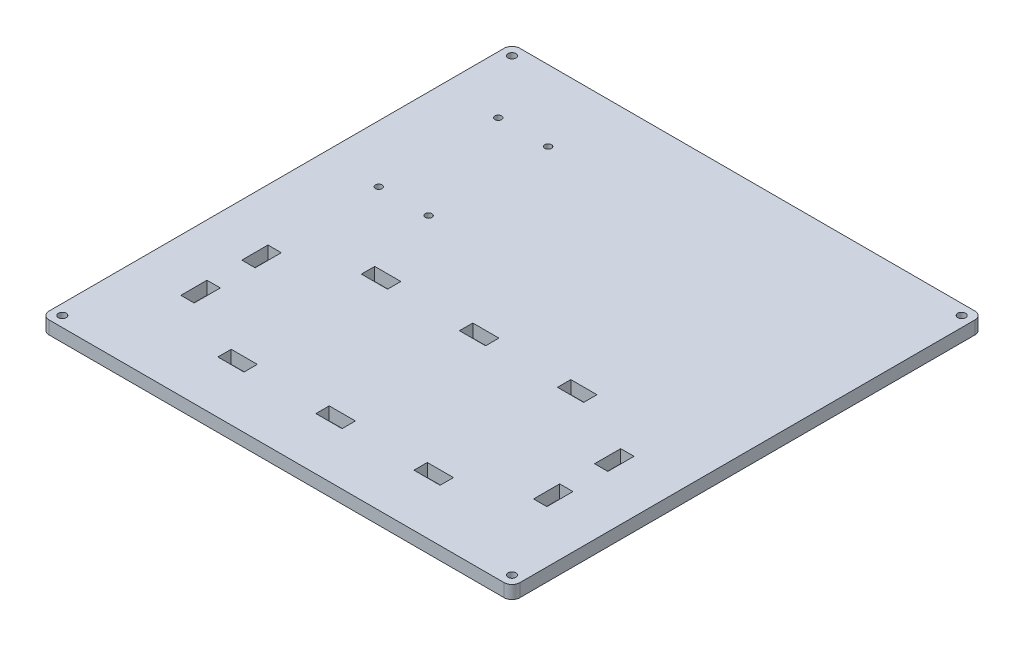
SolidWorks part; units mm, degrees
ref_plane "Front Plane" through (0, 0, 0) normal (0, 0, 1) x (1, 0, 0)
ref_plane "Top Plane" through (0, 0, 0) normal (0, 1, 0) x (1, 0, 0)
ref_plane "Right Plane" through (0, 0, 0) normal (1, 0, 0) x (0, 0, -1)
sketch "Sketch1" plane through (0, 0, 0) normal (0, 1, 0) x (1, 0, 0)
  line L1 (-90, -90) -> (90, -90)
  line L2 (-90, -90) -> (-90, 90)
  line L3 (-90, 90) -> (90, 90)
  line L4 (90, -90) -> (90, 90)
  line L5 (-90, -90) -> (90, 90) construction
  line L6 (-90, 90) -> (90, -90) construction
  line L7 (-70, 65.4) -> (-47.3, 65.4)
  line L8 (-70, 65.4) -> (-70, 14.6)
  line L9 (-70, 14.6) -> (-47.3, 14.6)
  line L10 (-47.3, 65.4) -> (-47.3, 14.6)
  line L11 (-70, 65.4) -> (-47.3, 14.6) construction
  line L12 (-70, 14.6) -> (-47.3, 65.4) construction
  circle A0 centre (-86, 86) radius 1.5
  circle A1 centre (86, 86) radius 1.5
  circle A2 centre (86, -86) radius 1.5
  circle A3 centre (-86, -86) radius 1.5
  circle A4 centre (-68.095, 62.86) radius 1.27
  circle A5 centre (-49.045, 62.86) radius 1.27
  circle A6 centre (-49.045, 17.14) radius 1.27
  circle A7 centre (-68.095, 17.14) radius 1.27
  point P0 (0, 0)
  point P6 (-58.65, 40)
  dimension "D7" = 3
  dimension "D8" = 4
  dimension "D11" = 2.54
  dimension "D13" = 2.54
  dimension "D17" = 2.54
  dimension "D20" = 4
  dimension "D1" = 180
  dimension "D2" = 180
  dimension "D3" = 22.7
  dimension "D4" = 50.8
  dimension "D5" = 24.6
  dimension "D6" = 20
  dimension "D9" = 2
  dimension "D12" = 1.905
  dimension "D16" = 4
  dimension "D18" = 4
  dimension "D19" = 4
  dimension "D10" = 2
  dimension "D14" = 2
  dimension "D15" = 2
extrude "Boss-Extrude1" add sketch "Sketch1" along normal blind 5 contours L1 L4 L3 L2 A3 A2 A1 A0 L7 L10 L9 L8 | L10 L7 L8 L9 A7 A6 A5 A4
sketch "Sketch3" plane through (0, 5, 0) normal (0, 1, 0) x (1, 0, 0)
  line L0 (90, -90) -> (90, 90) construction
  line L1 (20, 85) -> (80, 85)
  line L2 (20, 85) -> (20, 5)
  line L3 (20, 5) -> (80, 5)
  line L4 (80, 85) -> (80, 5)
  line L5 (-90, 90) -> (90, 90) construction
  dimension "D1" = 80
  dimension "D2" = 60
  dimension "D3" = 10
  dimension "D4" = 5
extrude "Boss-Extrude2" [suppressed] add sketch "Sketch3" along normal blind 5
sketch "Sketch4" plane through (0, 5, 0) normal (0, 1, 0) x (1, 0, 0)
  line L0 (-90, -90) -> (90, -90) construction
  line L5 (70, -60) -> (90, -60) construction
  line L6 (90, -90) -> (90, 90) construction
  line L7 (-32.5, -10) -> (-5, -10)
  line L8 (-70, -60) -> (-90, -60) construction
  line L9 (-42.5, -10) -> (-32.5, -10)
  line L10 (-42.5, -10) -> (-42.5, -15.1)
  line L11 (-42.5, -15.1) -> (-32.5, -15.1)
  line L12 (-32.5, -10) -> (-32.5, -15.1)
  line L13 (-5, -10) -> (5, -10)
  line L14 (-5, -10) -> (-5, -15.1)
  line L15 (-5, -15.1) -> (5, -15.1)
  line L16 (5, -10) -> (5, -15.1)
  line L17 (32.5, -10) -> (42.5, -10)
  line L18 (32.5, -10) -> (32.5, -15.1)
  line L19 (32.5, -15.1) -> (42.5, -15.1)
  line L20 (42.5, -10) -> (42.5, -15.1)
  line L21 (-90, -90) -> (-90, 90) construction
  line L22 (-42.5, -64.9) -> (-42.5, -70)
  line L23 (-70, -23.3333) -> (-64.9, -23.3333)
  line L24 (-70, -23.3333) -> (-70, -33.3333)
  line L25 (-70, -33.3333) -> (-64.9, -33.3333)
  line L26 (-64.9, -23.3333) -> (-64.9, -33.3333)
  line L31 (-70, -46.6667) -> (-64.9, -46.6667)
  line L32 (-70, -46.6667) -> (-70, -56.6667)
  line L33 (-70, -56.6667) -> (-64.9, -56.6667)
  line L34 (-64.9, -46.6667) -> (-64.9, -56.6667)
  line L35 (-42.5, -64.9) -> (-32.5, -64.9)
  line L36 (-32.5, -64.9) -> (-32.5, -70)
  line L37 (-42.5, -70) -> (-32.5, -70)
  line L38 (-5, -64.9) -> (-5, -70)
  line L39 (-5, -64.9) -> (5, -64.9)
  line L40 (5, -64.9) -> (5, -70)
  line L41 (-5, -70) -> (5, -70)
  line L42 (32.5, -64.9) -> (32.5, -70)
  line L43 (32.5, -64.9) -> (42.5, -64.9)
  line L44 (42.5, -64.9) -> (42.5, -70)
  line L45 (32.5, -70) -> (42.5, -70)
  line L46 (64.9, -23.3333) -> (64.9, -33.3333)
  line L47 (64.9, -23.3333) -> (70, -23.3333)
  line L48 (70, -23.3333) -> (70, -33.3333)
  line L49 (64.9, -33.3333) -> (70, -33.3333)
  line L54 (64.9, -46.6667) -> (64.9, -56.6667)
  line L55 (64.9, -46.6667) -> (70, -46.6667)
  line L56 (70, -46.6667) -> (70, -56.6667)
  line L57 (64.9, -56.6667) -> (70, -56.6667)
  line L58 (5, -10) -> (32.5, -10)
  line L59 (-70, -33.3333) -> (-70, -46.6667)
  line L60 (-70, -56.6667) -> (-70, -70)
  line L63 (-70, -23.3333) -> (-70, -10)
  line L64 (70, -33.3333) -> (70, -46.6667) construction
  line L65 (42.5, -10) -> (70, -10)
  line L70 (70, -70) -> (42.5, -70)
  line L71 (32.5, -70) -> (5, -70)
  line L72 (-5, -70) -> (-32.5, -70)
  line L73 (-42.5, -70) -> (-70, -70)
  line L78 (-70, -10) -> (-42.5, -10)
  dimension "D3" = 140
  dimension "D4" = 60
  dimension "D5" = 10
  dimension "D6" = 10
  dimension "D7" = 10
  dimension "D8" = 20
  dimension "D11" = 5.1
  dimension "D12" = 5.1
  dimension "D13" = 5.1
  dimension "D14" = 10
  dimension "D16" = 10
  dimension "D20" = 5.1
  dimension "D21" = 2
  dimension "D22" = 2
extrude "Cut-Extrude1" cut sketch "Sketch4" against normal up to next
fillet "Fillet1" radius 3 4 edges at (-90, 2.5, 90) (90, 2.5, 90) (-90, 2.5, -90) (90, 2.5, -90)
